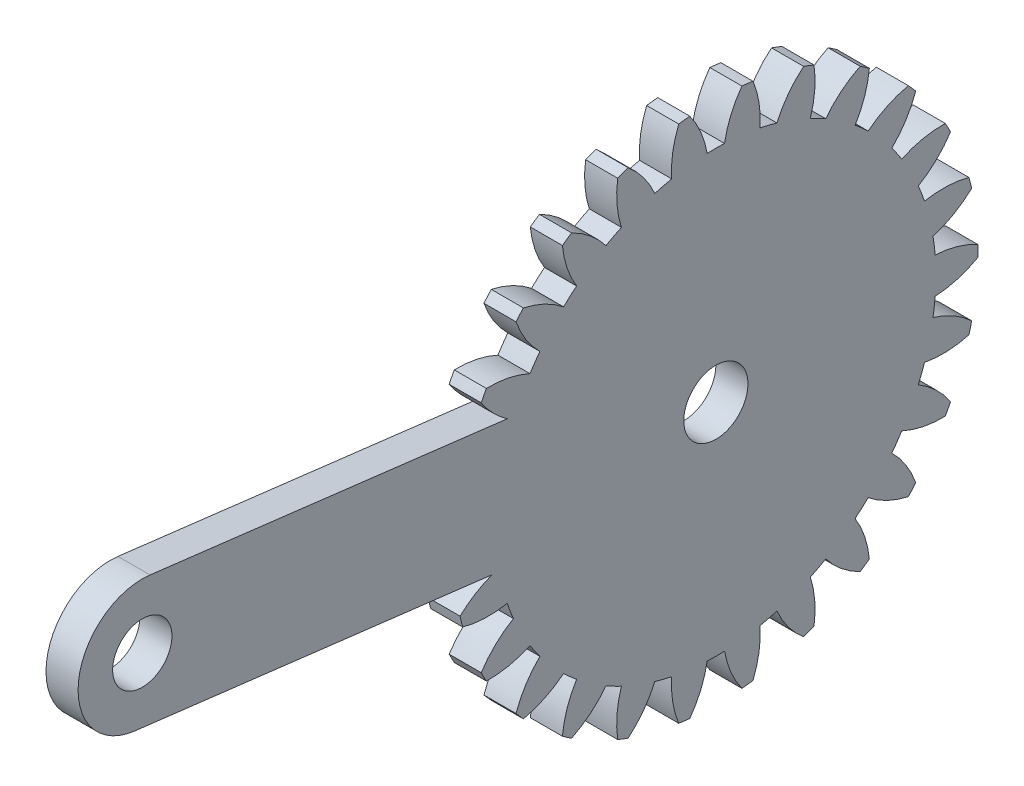
SolidWorks part; units mm, degrees
ref_plane "Plane1" through (0, 0, 0) normal (0, 0, 1) x (1, 0, 0)
ref_plane "Plane2" through (0, 0, 0) normal (0, 1, 0) x (1, 0, 0)
ref_plane "Plane3" through (0, 0, 0) normal (1, 0, 0) x (0, 0, -1)
sketch "HoldingSke" plane through (0, 0, 0) normal (0, 1, 0) x (1, 0, 0)
  line L0 (0, 0) -> (0.5136, -0.2505)
  line L1 (-15, 0) -> (100, 0) construction
  line L2 (0, 0) -> (-2.1039, 2.3779)
  line L3 (0, 0) -> (-11.863, 4.5341)
  line L4 (0, 0) -> (7.762, 3.7858)
  line L5 (0, 0) -> (-46.8476, -17.4728)
  line L6 (0, 0) -> (-2.4869, -1.6779)
  line L7 (-2.1039, 2.3779) -> (8.6586, 51.2059)
  line L8 (-76.2, 54.61) -> (-75.2, 54.61)
  line L9 (-71.009, 38.7566) -> (-53.1078, 45.2721)
  line L10 (-76.2, 71.12) -> (104.1128, 71.12)
  line L11 (0, 0) -> (-3, 0)
  line L12 (-76.2, 101.6) -> (-76.147, 101.6)
  line L13 (24.9733, 27.94) -> (52.9518, 28.4284)
  line L14 (24.9733, 27.94) -> (24.9743, 27.94)
  line L15 (24.9733, 27.94) -> (100.4006, 29.5858)
  line L16 (-63.627, -1.75) -> (-12.827, -1.75)
  circle A0 centre (0, 0) radius 3
  circle A1 centre (0, 0) radius 20.5615
  circle A2 centre (0, 0) radius 37.5
  circle A3 centre (0, 0) radius 3
  dimension "MHD" = 41.123
  dimension "Hub_dia" = 75
  dimension "Bore" = 6
  dimension "MBD" = 6
  dimension "Num_teeth" = 26
  dimension "Pitch" = 0.5714
  dimension "Overall_len" = 50
  dimension "Show_teeth" = 26
  dimension "Thickness" = 3
  dimension "OAL" = 50.0001
  dimension "T_dim" = 1
  dimension "Ap" = 20
  dimension "H" = 19.05
  dimension "Pitch_radius" = 180.3128
  dimension "Width" = 3
  dimension "Backlash" = 0.053
  dimension "Addendum_fac" = 1
  dimension "Dedendum_fac" = 1.25
  dimension "Clearance_fac" = 0.25
  dimension "Dedendum_add" = 0.001
  dimension "Module" = 1.75
sketch "BasProSke" plane through (0, 0, 0) normal (0, 1, 0) x (1, 0, 0)
  line L0 (-10, 0) -> (60, 0) construction
  line L1 (0, 0) -> (0, 24.5)
  line L2 (0, 0) -> (3, 0)
  line L3 (3, 0) -> (3, 24.5)
  line L4 (3, 24.5) -> (0, 24.5)
  dimension "Thickness" = 3
  dimension "Diameter" = 49
revolve "Base-Revolve" add sketch "BasProSke" angle 360 about L0
sketch "TooCutSke" plane through (0, 0, 0) normal (1, 0, 0) x (0, 0, -1)
  line L1 (0, 0) -> (0, 107) construction
  line L2 (0, 0) -> (-1.4663, 22.7027) construction
  line L3 (0, 0) -> (-5.4757, 45.0966) construction
  line L4 (-1.4663, 22.7027) -> (-2.7379, 22.5483) construction
  arc A0 (0.8134, 20.5454) -> (-0.8134, 20.5454) centre (0, 0) ccw
  arc A1 (2.4537, 24.4024) -> (-2.4537, 24.4024) centre (0, 0) ccw
  circle A2 centre (0, 0) radius 22.75 construction
  circle A3 centre (0, 0) radius 21.378 construction
  arc A4 (-0.8134, 20.5454) -> (-2.4537, 24.4024) centre (-9.7827, 19.0084) ccw
  arc A5 (2.4537, 24.4024) -> (0.8134, 20.5454) centre (9.7827, 19.0084) ccw
  dimension "Root_dia" = 41.123
  dimension "Overcut_dia" = 49.0508
  dimension "Pitch_dia" = 45.5
  dimension "Base_dia" = 42.756
  dimension "Flank_rad" = 9.1
  dimension "Half_ang" = 6.923
  dimension "Half_CT" = 1.2809
extrude "ToothCut" cut sketch "TooCutSke" along normal through all
fillet "Breaks" [suppressed] radius 0.035
fillet "RootFillets" [suppressed] radius 0.4385
pattern_circular "TeethCuts" count 26 every 13.846 about axis through (-10, 0, 0) along (1, 0, 0) of "ToothCut", "RootFillets", "Breaks"
sketch "HubNeaOneSke" plane through (0, 0, 0) normal (-1, 0, 0) x (0, 0, 1)
  circle A0 centre (0, 0) radius 20.5615
  dimension "Diameter" = 41.123
extrude "HubNearOne" [suppressed] add sketch "HubNeaOneSke" along normal blind 47.0001
sketch "HubNeaBotSke" plane through (0, 0, 0) normal (-1, 0, 0) x (0, 0, 1)
  circle A0 centre (0, 0) radius 20.5615
  dimension "Diameter" = 41.123
extrude "HubNearBoth" [suppressed] add sketch "HubNeaBotSke" along normal blind 23.5
ref_plane "FarPln" through (3, 0, 0) normal (1, 0, 0) x (0, 0, -1)
sketch "HubFarSke" plane through (3, 0, 0) normal (1, 0, 0) x (0, 0, -1)
  circle A0 centre (0, 0) radius 20.5615
  dimension "Diameter" = 41.123
extrude "HubFar" [suppressed] add sketch "HubFarSke" along normal blind 23.5
sketch "BorSke" plane through (0, 0, 0) normal (1, 0, 0) x (0, 0, -1)
  circle A0 centre (0, 0) radius 3
  dimension "Diameter" = 6
extrude "Bore" cut sketch "BorSke" along normal mid plane 100.0001
sketch "KeySke" plane through (0, 0, 0) normal (1, 0, 0) x (0, 0, -1)
  line L0 (-1, 0) -> (-1, 4)
  line L1 (-1, 4) -> (1, 4)
  line L2 (1, 4) -> (1, 0)
  line L3 (0, 0) -> (0, 34) construction
  line L4 (-1, 0) -> (1, 0)
  dimension "Offset" = 4
  dimension "Width" = 2
extrude "Keyway" [suppressed] cut sketch "KeySke" along normal mid plane 100.0001
pattern_circular "Keyway2" [suppressed] count 2 every 90 about axis through (-10, 0, 0) along (1, 0, 0)
sketch "Sketch1" plane through (0, 0, 0) normal (1, 0, 0) x (0, 0, -1)
  line L0 (0, 0) -> (2.9531, 24.3214) construction
  line L1 (0, 0) -> (-53.6063, 6.509) construction
  line L2 (-0.7232, -5.9563) -> (-54.3295, 0.5527)
  line L3 (0.7232, 5.9563) -> (-52.8831, 12.4652)
  arc A0 (3.4687, 24.2532) -> (2.4362, 24.3786) centre (0, 0) ccw construction
  circle A1 centre (-53.6063, 6.509) radius 2.7705
  arc A2 (-0.7232, -5.9563) -> (0.7232, 5.9563) centre (0, 0) ccw
  arc A3 (-52.8831, 12.4652) -> (-54.3295, 0.5527) centre (-53.6063, 6.509) ccw
  circle A4 centre (0, 0) radius 3
  point P8 (-26.8031, 3.2545)
  dimension "D1" = 54
  dimension "D2" = 11.9125
extrude "Boss-Extrude1" add sketch "Sketch1" along normal blind 3
equation "' \"Module@HoldingSke\" = 6.35"
equation "' \"Num_teeth@HoldingSke\" = 12"
equation "' \"Ap@HoldingSke\" =  20"
equation "' \"Ap@HoldingSke\" = 20"
equation "' \"Width@HoldingSke\" = 0.5 * 25.4"
equation "' \"Hub_dia@HoldingSke\"= 1 * 25.4"
equation "' \"Hub_dia@HoldingSke\" = 1 * 25.4"
equation "' \"Overall_len@HoldingSke\" = 1.0 * 25.4"
equation "' \"Bore@HoldingSke\" = 0.75 * 25.4"
equation "' \"T_dim@HoldingSke\" = 0.1 * 25.4"
equation "' \"Width@KeySke\" = 0.25 * 25.4"
equation "' \"Show_teeth@HoldingSke\" = 13"
equation "' \"Backlash@HoldingSke\" = 0.009 * 25.4"
equation "' \"Addendum_fac@HoldingSke\" = 1.0"
equation "' \"Dedendum_fac@HoldingSke\" = 1.25"
equation "' \"Dedendum_add@HoldingSke\" = 0.00005 * 25.4"
equation "' \"Clearance_fac@HoldingSke\" = 0.25"
equation "\"Pitch@HoldingSke\" = 1 / \"Module@HoldingSke\""
equation "\"Overcut_dia@TooCutSke\" = (\"Num_teeth@HoldingSke\" + 2 * \"Addendum_fac@HoldingSke\") / \"Pitch@HoldingSke\" + 0.002 * 25.4"
equation "\"Pitch_dia@TooCutSke\" = \"Num_teeth@HoldingSke\" / \"Pitch@HoldingSke\""
equation "\"Base_dia@TooCutSke\" = \"Num_teeth@HoldingSke\" / \"Pitch@HoldingSke\" * cos((\"Ap@HoldingSke\"  * 3.14159265 / 180))"
equation "\"Root_dia@TooCutSke\" = (\"Num_teeth@HoldingSke\" + 2) / \"Pitch@HoldingSke\" - 2 * (\"Addendum_fac@HoldingSke\" + \"Dedendum_fac@HoldingSke\") / \"Pitch@HoldingSke\" - \"Dedendum_add@HoldingSke\" * 2"
equation "\"Half_ang@TooCutSke\" = 180 / \"Num_teeth@HoldingSke\""
equation "\"Half_CT@TooCutSke\" = \"Num_teeth@HoldingSke\" / \"Pitch@HoldingSke\" * sin((3.14159265 / 2 / \"Num_teeth@HoldingSke\")) / 2 - 7 * \"Backlash@HoldingSke\" / 4"
equation "\"Flank_rad@TooCutSke\" = \"Num_teeth@HoldingSke\" / \"Pitch@HoldingSke\" / 5"
equation "\"Radius@RootFillets\" = \"Clearance_fac@HoldingSke\" / \"Pitch@HoldingSke\" + \"Dedendum_add@HoldingSke\""
equation "\"Break_rad@Breaks\" = 0.02 / \"Pitch@HoldingSke\""
equation "\"Thickness@HoldingSke\" = \"Width@HoldingSke\""
equation "\"OAL@HoldingSke\" = \"Thickness@HoldingSke\""
equation "\"MHD@HoldingSke\" = (\"Num_teeth@HoldingSke\" + 2) / \"Pitch@HoldingSke\" - 2 * (\"Addendum_fac@HoldingSke\" + \"Dedendum_fac@HoldingSke\")  / \"Pitch@HoldingSke\" - \"Dedendum_add@HoldingSke\" * 2"
equation "\"MBD@HoldingSke\" = (\"Num_teeth@HoldingSke\" + 2) / \"Pitch@HoldingSke\" - 2 * (\"Addendum_fac@HoldingSke\" + \"Dedendum_fac@HoldingSke\")  / \"Pitch@HoldingSke\" - \"Dedendum_add@HoldingSke\" * 2 - 0.002 * 25.4"
equation "\"MHD@HoldingSke\" = ((sgn( \"MHD@HoldingSke\" - \"Hub_dia@HoldingSke\" )-1)*( \"MHD@HoldingSke\" - \"Hub_dia@HoldingSke\" ))/-2+ \"Hub_dia@HoldingSke\""
equation "\"MBD@HoldingSke\" = ((sgn( \"MBD@HoldingSke\" - \"Bore@HoldingSke\" )-1)*( \"MBD@HoldingSke\" - \"Bore@HoldingSke\" ))/-2+ \"Bore@HoldingSke\""
equation "\"OAL@HoldingSke\" = ((sgn( \"OAL@HoldingSke\" - \"Overall_len@HoldingSke\" )+1)*( \"OAL@HoldingSke\" - \"Overall_len@HoldingSke\" ))/2 + \"Overall_len@HoldingSke\" + 0.000002 * 25.4"
equation "\"Num_teeth@TeethCuts\" = int( \"Show_teeth@HoldingSke\" ) + 1"
equation "\"Num_teeth@TeethCuts\" = ((sgn( \"Num_teeth@TeethCuts\" - \"Num_teeth@HoldingSke\" )-1)*( \"Num_teeth@TeethCuts\" - \"Num_teeth@HoldingSke\" ))/-2+ \"Num_teeth@HoldingSke\""
equation "\"Num_teeth@TeethCuts\" = ((sgn( \"Num_teeth@TeethCuts\" - 2.0)+1)*( \"Num_teeth@TeethCuts\" - 2.0))/2 +2.0"
equation "\"Angle@TeethCuts\" = 360.0 / \"Num_teeth@HoldingSke\""
equation "\"Diameter@BasProSke\" = (\"Num_teeth@HoldingSke\" + 2 * \"Addendum_fac@HoldingSke\") / \"Pitch@HoldingSke\""
equation "\"Thickness@BasProSke\"  = \"Thickness@HoldingSke\""
equation "' \"Fillet_rad@BasProSke\" =  \"Thickness@HoldingSke\" * 0.05"
equation "' \"Fillet_rad@BasProSke\" = \"Thickness@HoldingSke\" * 0.05"
equation "\"MHD@HoldingSke\" = ((sgn( \"MHD@HoldingSke\" - \"Root_dia@TooCutSke\" )-1)*( \"MHD@HoldingSke\" - \"Root_dia@TooCutSke\" ))/-2+ \"Root_dia@TooCutSke\""
equation "\"Diameter@HubNeaOneSke\" = \"MHD@HoldingSke\""
equation "\"Length@HubNearOne\" = \"OAL@HoldingSke\" - \"Thickness@BasProSke\""
equation "\"Diameter@HubNeaBotSke\" = \"MHD@HoldingSke\""
equation "\"Length@HubNearBoth\" = ( \"OAL@HoldingSke\" - \"Thickness@BasProSke\" ) / 2.0"
equation "\"Thickness@FarPln\" = \"Thickness@BasProSke\""
equation "\"Diameter@HubFarSke\" = \"MHD@HoldingSke\""
equation "\"Length@HubFar\" = ( \"OAL@HoldingSke\" - \"Thickness@BasProSke\" ) / 2.0"
equation "\"Diameter@BorSke\" = \"MBD@HoldingSke\""
equation "\"D1@Bore\" = \"OAL@HoldingSke\" * 2.0"
equation "\"D1@Keyway\" = \"OAL@HoldingSke\" * 2.0"
equation "\"Offset@KeySke\" = \"T_dim@HoldingSke\" + \"MBD@HoldingSke\" / 2.0"
